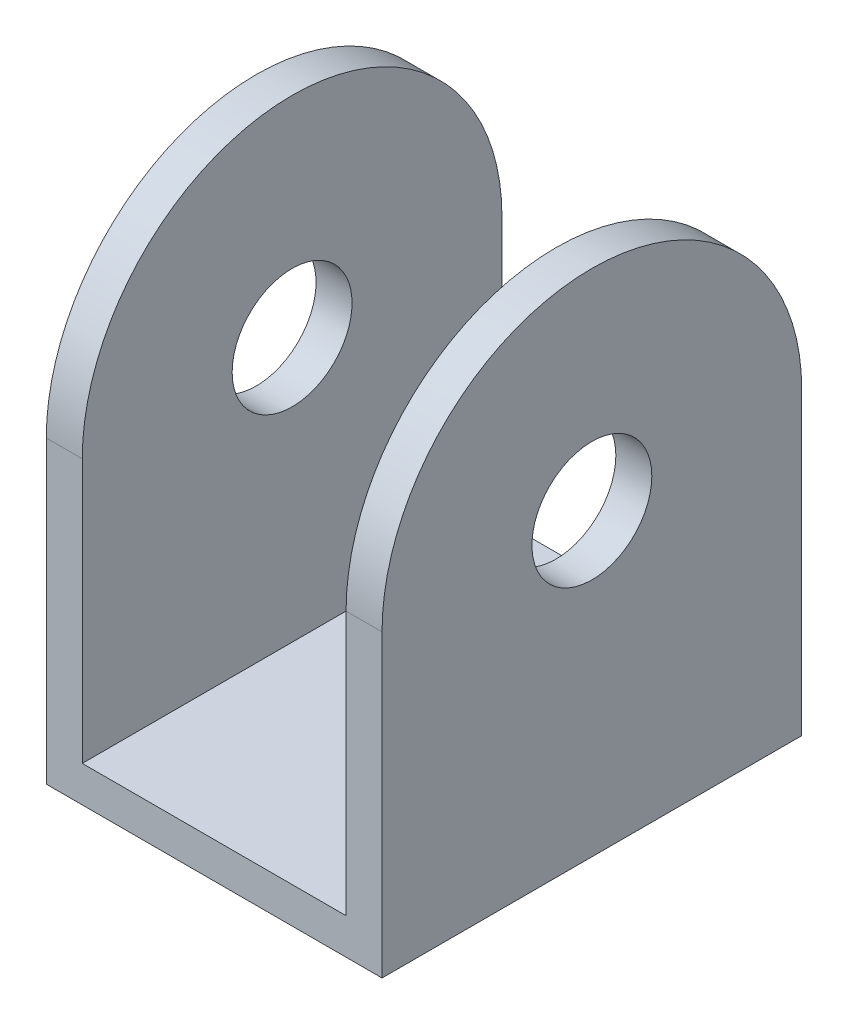
SolidWorks part; units mm, degrees
ref_plane "Front Plane" through (0, 0, 0) normal (0, 0, 1) x (1, 0, 0)
ref_plane "Top Plane" through (0, 0, 0) normal (0, 1, 0) x (1, 0, 0)
ref_plane "Right Plane" through (0, 0, 0) normal (1, 0, 0) x (0, 0, -1)
sketch "Sketch1" plane through (0, 0, 0) normal (0, 1, 0) x (1, 0, 0)
  line L1 (-56.186, 17.4186) -> (-34.186, 17.4186)
  line L2 (-56.186, 17.4186) -> (-56.186, -17.5814)
  line L3 (-56.186, -17.5814) -> (-34.186, -17.5814)
  line L4 (-34.186, 17.4186) -> (-34.186, -17.5814)
  dimension "D1" = 22
  dimension "D2" = 35
extrude "Boss-Extrude1" add sketch "Sketch1" along normal blind 3
sketch "Sketch2" plane through (-34.186, 0, 0) normal (1, 0, 0) x (0, 0, -1)
  line L1 (-17.5814, 0) -> (17.4186, 0)
  line L2 (-17.5814, 0) -> (-17.5814, 25)
  line L3 (-17.5814, 25) -> (17.4186, 25)
  line L4 (17.4186, 0) -> (17.4186, 25)
  circle A0 centre (-0.0814, 25) radius 17.5
  circle A1 centre (-0.0814, 25) radius 5
  line M3 (-17.5814, 0) -> (17.4186, 0)
  line M4 (17.4186, 0) -> (17.4186, 3)
  line M5 (17.4186, 3) -> (-17.5814, 3)
  line M6 (-17.5814, 3) -> (-17.5814, 0)
  dimension "D1" = 25
  dimension "D2" = 35
sketch "Sketch4" plane through (-56.186, 0, 0) normal (-1, 0, 0) x (0, 0, 1)
  line L1 (-17.4186, 0) -> (17.5814, 0)
  line L2 (-17.4186, 0) -> (-17.4186, 25)
  line L3 (-17.4186, 25) -> (17.5814, 25)
  line L4 (17.5814, 0) -> (17.5814, 25)
  circle A0 centre (0.0814, 25) radius 17.5
  circle A1 centre (0.0814, 25) radius 5
  line M3 (-17.4186, 0) -> (17.5814, 0)
  line M4 (17.5814, 0) -> (17.5814, 3)
  line M5 (17.5814, 3) -> (-17.4186, 3)
  line M6 (-17.4186, 3) -> (-17.4186, 0)
  dimension "D1" = 25
  dimension "D2" = 35
extrude "Boss-Extrude6" add sketch "Sketch2" along normal blind 3 contours A1 L3 A0 | A1 L3 A0 | A0 L2 L4 M5 | M6 M3 M4 M5
extrude "Boss-Extrude7" add sketch "Sketch4" along normal blind 3 contours A1 L3 A0 | A1 L3 A0 | A0 L2 L4 M5 | M6 M3 M4 M5
